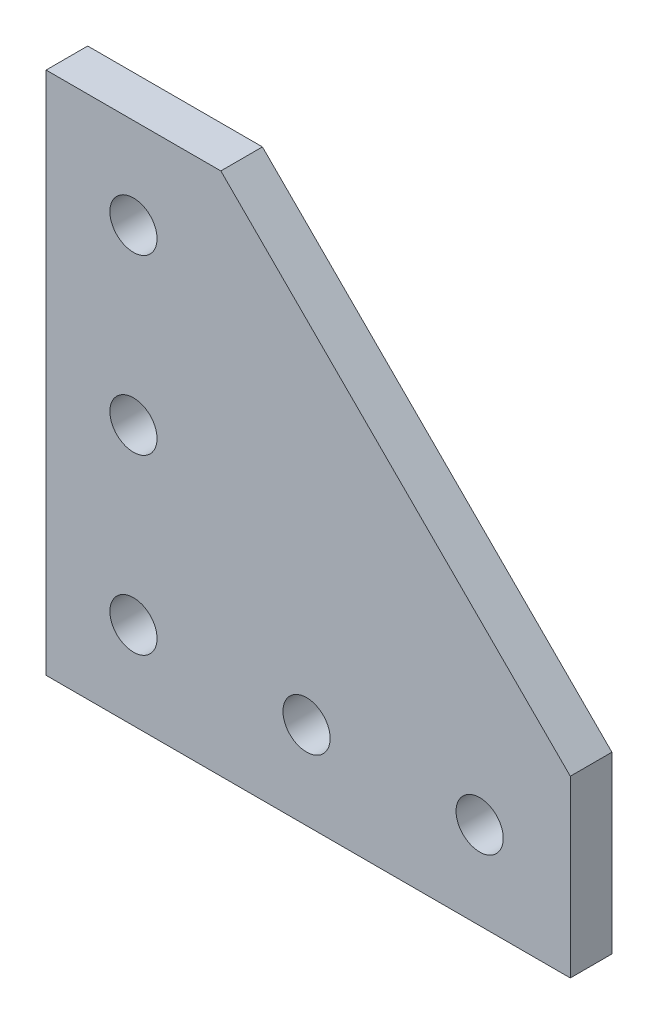
SolidWorks part; units mm, degrees
ref_plane "Front Plane" through (0, 0, 0) normal (0, 0, 1) x (1, 0, 0)
ref_plane "Top Plane" through (0, 0, 0) normal (0, 1, 0) x (1, 0, 0)
ref_plane "Right Plane" through (0, 0, 0) normal (1, 0, 0) x (0, 0, -1)
sketch "Sketch1" plane through (0, 0, 0) normal (0, 0, 1) x (1, 0, 0)
  line L0 (0, 0) -> (0, 60)
  line L1 (10, 10) -> (29.812, 10) construction
  line L2 (29.812, 10) -> (49.624, 10) construction
  line L3 (10, 10) -> (10, 29.812) construction
  line L4 (60, 20) -> (20, 60)
  line L5 (60, 0) -> (0, 0)
  line L6 (10, 29.812) -> (10, 49.624) construction
  line L7 (60, 20) -> (60, 0)
  line L8 (0, 60) -> (20, 60)
  circle A0 centre (10, 10) radius 2.7
  circle A1 centre (29.812, 10) radius 2.7
  circle A2 centre (49.624, 10) radius 2.7
  circle A3 centre (10, 29.812) radius 2.7
  circle A4 centre (10, 49.624) radius 2.7
  point P1 (11.1673, 11.5275)
  point P12 (60, 10)
  point P17 (10, 60)
  point P18 (10, 49.8862)
  dimension "D1" = 60
  dimension "D2" = 20
  dimension "D3" = 5.4
  dimension "D4" = 19.812
extrude "Boss-Extrude1" add sketch "Sketch1" along normal mid plane 4.7625
